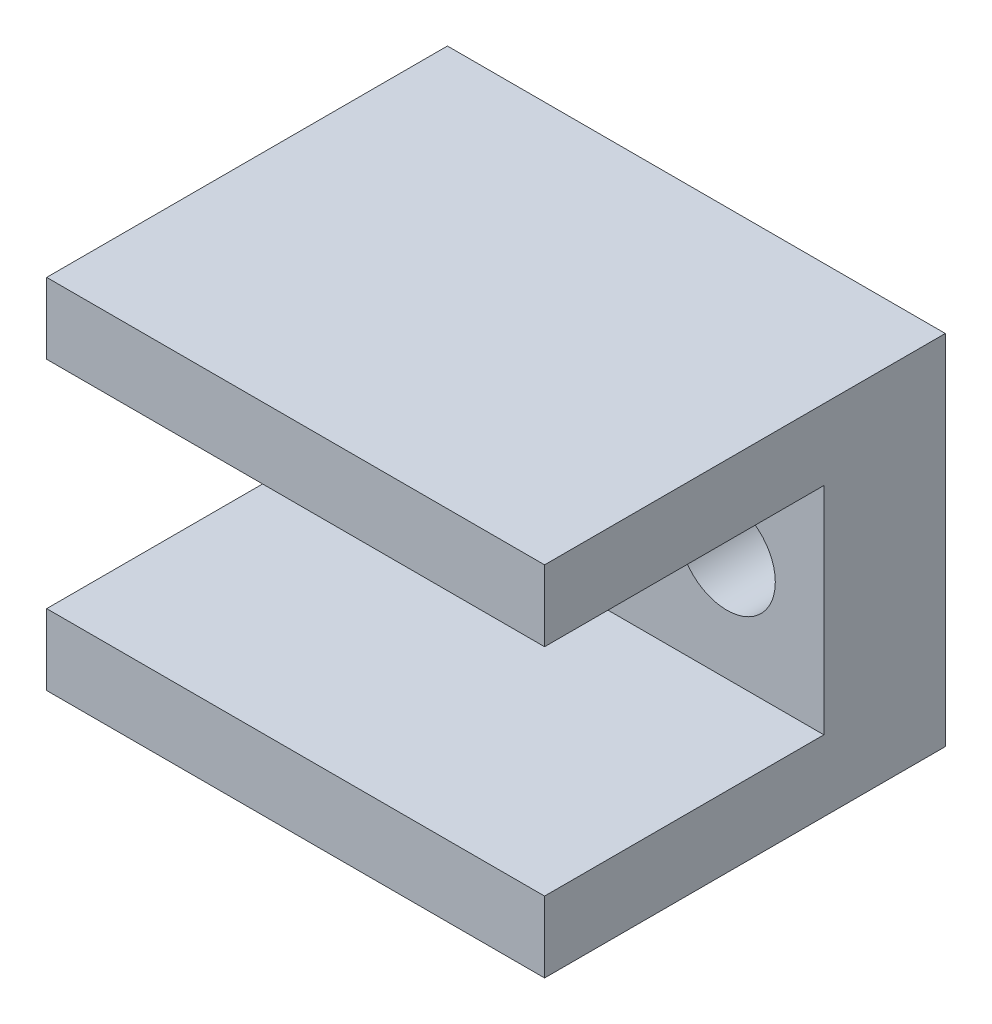
SolidWorks part; units mm, degrees
ref_plane "Front Plane" through (0, 0, 0) normal (0, 0, 1) x (1, 0, 0)
ref_plane "Top Plane" through (0, 0, 0) normal (0, 1, 0) x (1, 0, 0)
ref_plane "Right Plane" through (0, 0, 0) normal (1, 0, 0) x (0, 0, -1)
sketch "Sketch1" plane through (0, 0, 0) normal (0, 0, 1) x (1, 0, 0)
  line L1 (-20.5, -14.732) -> (20.5, -14.732)
  line L2 (-20.5, -14.732) -> (-20.5, 14.732)
  line L3 (-20.5, 14.732) -> (20.5, 14.732)
  line L4 (20.5, -14.732) -> (20.5, 14.732)
  line L5 (-20.5, -14.732) -> (20.5, 14.732) construction
  line L6 (-20.5, 14.732) -> (20.5, -14.732) construction
  point P0 (0, 0)
  dimension "D1" = 29.464
  dimension "D2" = 41
extrude "Boss-Extrude1" add sketch "Sketch1" along normal blind 10 contours L3 L4 L1 L2
sketch "Sketch2" plane through (0, 0, 10) normal (0, 0, 1) x (1, 0, 0)
  line L0 (55, 0) -> (-55, 0) construction
  line L1 (-20.5, 8.89) -> (20.5, 8.89)
  line L2 (-20.5, 8.89) -> (-20.5, 14.732)
  line L3 (-20.5, 14.732) -> (20.5, 14.732)
  line L4 (20.5, 8.89) -> (20.5, 14.732)
  line L5 (-20.5, 8.89) -> (20.5, 14.732) construction
  line L6 (-20.5, 14.732) -> (20.5, 8.89) construction
  line L11 (-20.5, 14.732) -> (20.5, 14.732) construction
  line L12 (20.5, -14.732) -> (20.5, 14.732) construction
  line L13 (-20.5, -8.89) -> (20.5, -14.732) construction
  line L14 (-20.5, -14.732) -> (20.5, -8.89) construction
  line L15 (-20.5, -14.732) -> (20.5, -14.732)
  line L16 (20.5, -8.89) -> (20.5, -14.732)
  line L17 (-20.5, -8.89) -> (20.5, -8.89)
  line L18 (-20.5, -8.89) -> (-20.5, -14.732)
  point P0 (0, 11.811)
  point P15 (0, -11.811)
  dimension "D1" = 17.78
extrude "Boss-Extrude2" add sketch "Sketch2" along normal blind 23
sketch "Sketch3" plane through (0, 0, 10) normal (0, 0, 1) x (1, 0, 0)
  line L0 (-12.5, 0) -> (12.5, 0) construction
  circle A0 centre (-12.5, 0) radius 4
  circle A1 centre (12.5, 0) radius 4
  point P4 (0, 0)
  point P6 (0, 0)
  dimension "D1" = 8
  dimension "D2" = 25
extrude "Cut-Extrude1" cut sketch "Sketch3" against normal up to next
